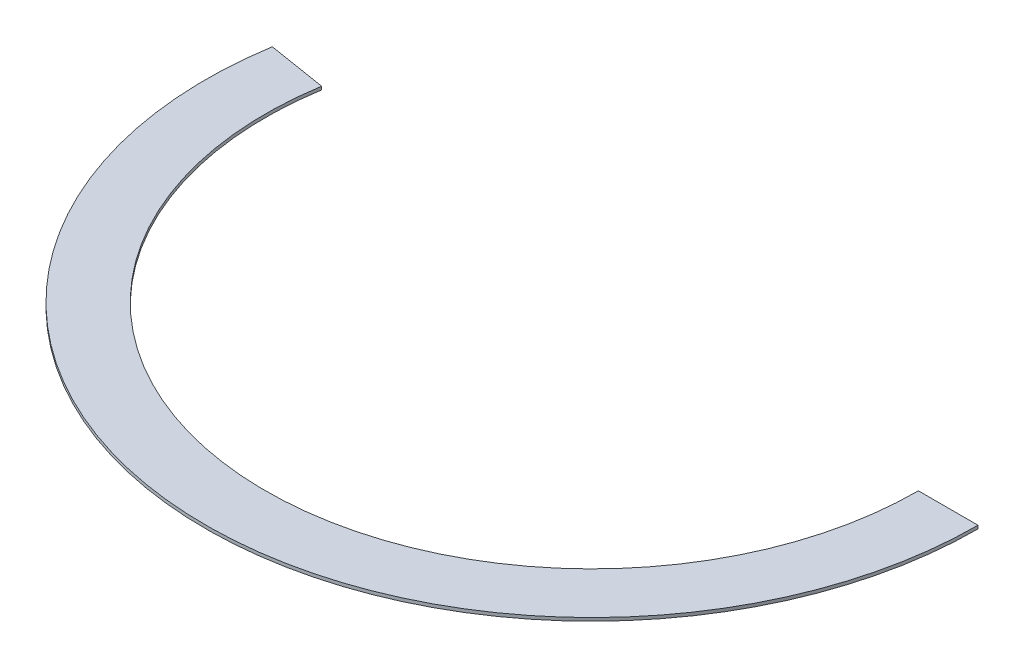
SolidWorks part; units mm, degrees
ref_plane "Front Plane" through (0, 0, 0) normal (0, 0, 1) x (1, 0, 0)
ref_plane "Top Plane" through (0, 0, 0) normal (0, 1, 0) x (1, 0, 0)
ref_plane "Right Plane" through (0, 0, 0) normal (1, 0, 0) x (0, 0, -1)
sketch "Sketch3" plane through (0, 0, 0) normal (0, 1, 0) x (1, 0, 0)
  line L0 (-70.3098, 11.3499) -> (-83.1437, 13.4217)
  line L1 (71.22, 0) -> (84.22, 0)
  arc A0 (-83.1437, 13.4217) -> (84.22, 0) centre (0, 0) ccw
  arc A1 (71.22, 0) -> (-70.3098, 11.3499) centre (0, 0) cw
  dimension "D1" = 13
  dimension "D2" = 84.22
  dimension "D3" = 170.83
extrude "Boss-Extrude1" add sketch "Sketch3" along normal blind 0.7
